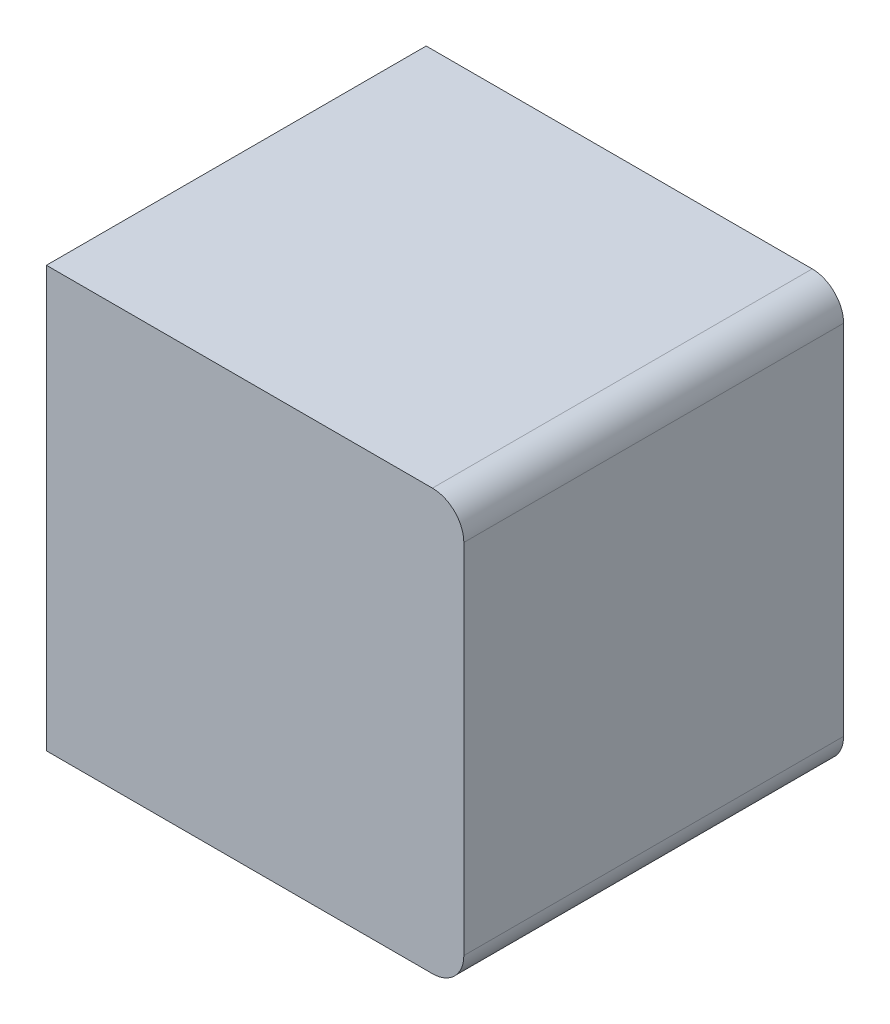
SolidWorks part; units mm, degrees
ref_plane "前视基准面" through (0, 0, 0) normal (0, 0, 1) x (1, 0, 0)
ref_plane "上视基准面" through (0, 0, 0) normal (0, 1, 0) x (1, 0, 0)
ref_plane "右视基准面" through (0, 0, 0) normal (1, 0, 0) x (0, 0, -1)
sketch "草图1" plane through (0, 0, 0) normal (0, 0, 1) x (1, 0, 0)
  line L1 (-38.25, 29.3282) -> (23.25, 29.3282)
  line L2 (-38.25, 29.3282) -> (-38.25, -37.6718)
  line L3 (-38.25, -37.6718) -> (23.25, -37.6718)
  line L4 (28.25, 24.3282) -> (28.25, -32.6718)
  arc A0 (23.25, -37.6718) -> (28.25, -32.6718) centre (23.25, -32.6718) ccw
  arc A1 (28.25, 24.3282) -> (23.25, 29.3282) centre (23.25, 24.3282) ccw
  point P6 (28.25, -37.6718)
  point P9 (28.25, 29.3282)
  dimension "D3" = 5
  dimension "D1" = 66.5
  dimension "D2" = 67
extrude "凸台-拉伸1" add sketch "草图1" against normal blind 60.5 contours L4 A0 L3 L2 L1 A1
